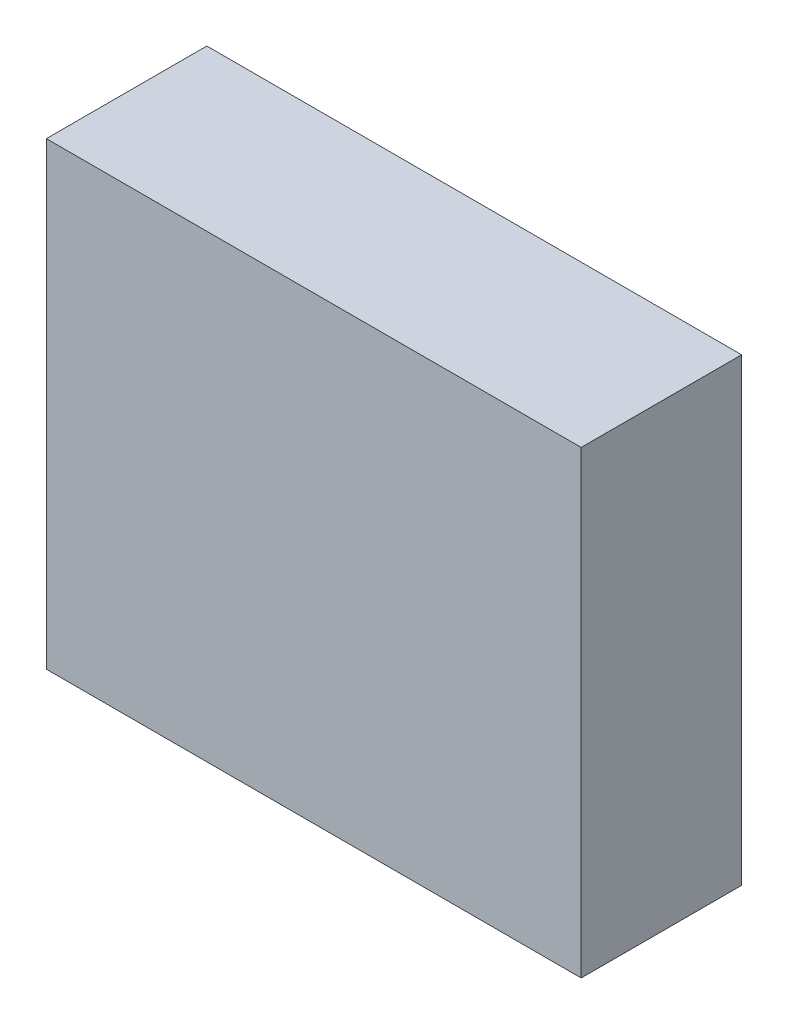
SolidWorks part; units mm, degrees
ref_plane "Front Plane" through (0, 0, 0) normal (0, 0, 1) x (1, 0, 0)
ref_plane "Top Plane" through (0, 0, 0) normal (0, 1, 0) x (1, 0, 0)
ref_plane "Right Plane" through (0, 0, 0) normal (1, 0, 0) x (0, 0, -1)
sketch "Sketch1" plane through (0, 0, 0) normal (0, 0, 1) x (1, 0, 0)
  line L0 (-3.55, -3.05) -> (-3.55, 3.05)
  line L1 (-3.55, 3.05) -> (3.55, 3.05)
  line L2 (3.55, 3.05) -> (3.55, -3.05)
  line L3 (3.55, -3.05) -> (-3.55, -3.05)
extrude "Component_Outline" add sketch "Sketch1" along normal blind 2.13 separate body
sketch3d "3DSketch1"
  line L0 (0, 0, 0) -> (1, 0, 0)
  line L1 (0, 0, 0) -> (0, 1, 0)
  line L2 (0, 0, 0) -> (0, 0, 1)
  point P0 (0, 0, 0)
